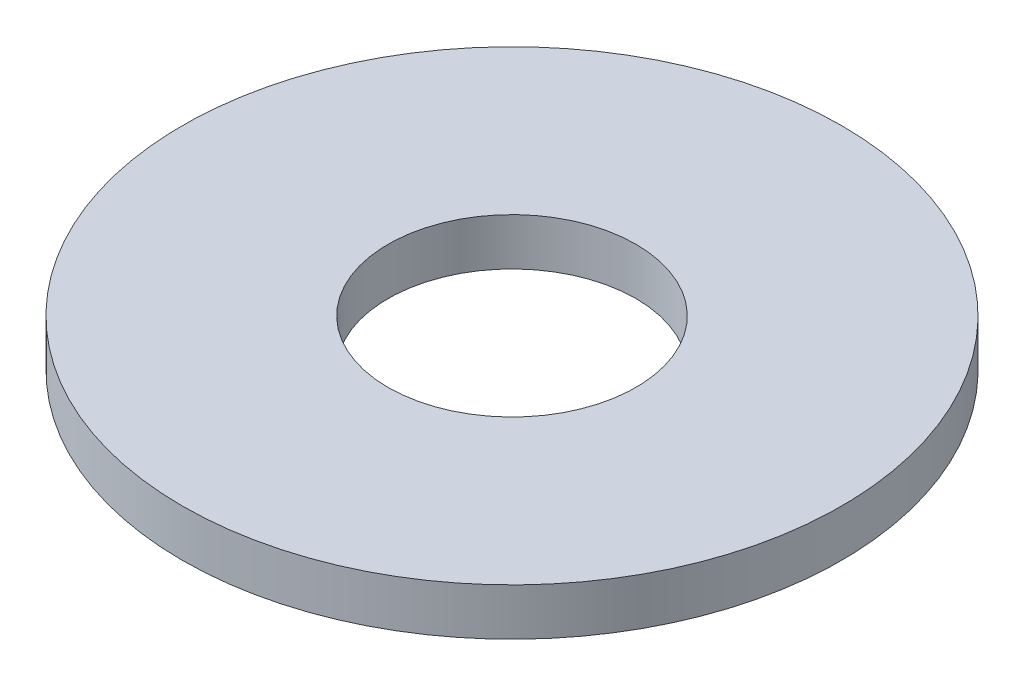
SolidWorks part; units mm, degrees
material "Nylon 6/10"
ref_plane "Front Plane" through (0, 0, 0) normal (0, 0, 1) x (1, 0, 0)
ref_plane "Top Plane" through (0, 0, 0) normal (0, 1, 0) x (1, 0, 0)
ref_plane "Right Plane" through (0, 0, 0) normal (1, 0, 0) x (0, 0, -1)
sketch "Sketch1" plane through (0, 0, 0) normal (0, 1, 0) x (1, 0, 0)
  circle A0 centre (0, 0) radius 1.0033
  circle A1 centre (0, 0) radius 2.667
  dimension "D1" = 2.0066
  dimension "D2" = 5.334
extrude "Boss-Extrude1" add sketch "Sketch1" along normal blind 0.381
